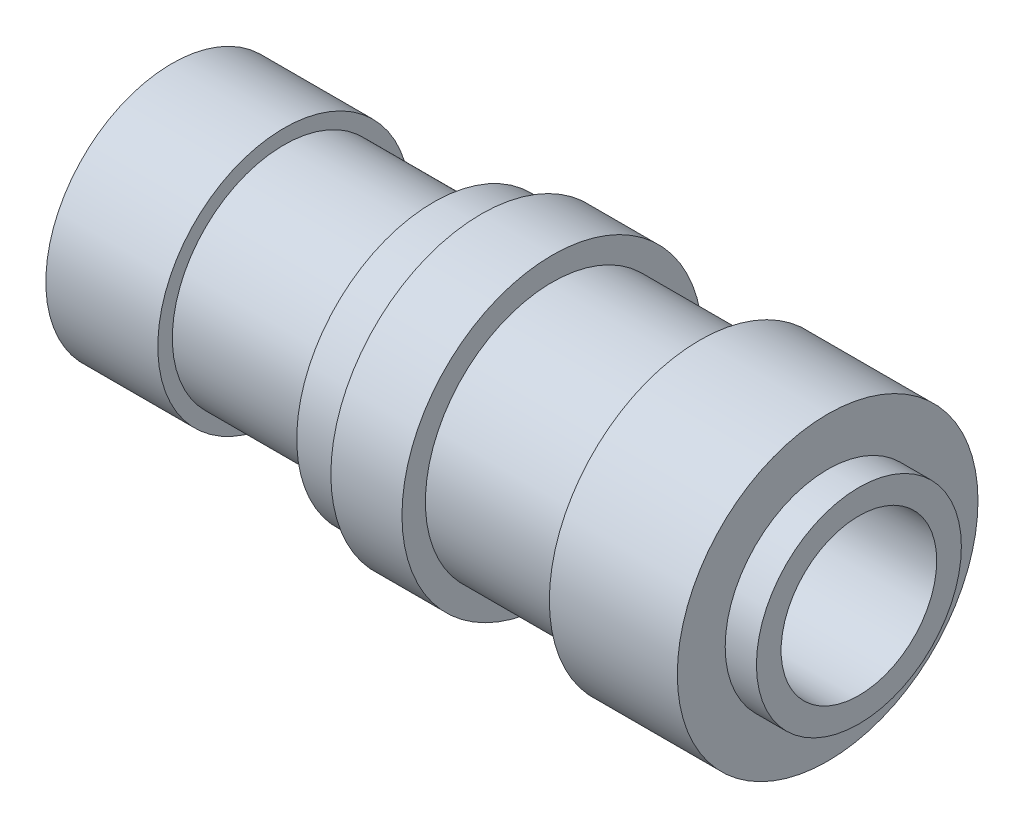
SolidWorks part; units mm, degrees
ref_plane "Front Plane" through (0, 0, 0) normal (0, 0, 1) x (1, 0, 0)
ref_plane "Top Plane" through (0, 0, 0) normal (0, 1, 0) x (1, 0, 0)
ref_plane "Right Plane" through (0, 0, 0) normal (1, 0, 0) x (0, 0, -1)
sketch "Sketch2" plane through (0, 0, 0) normal (0, 1, 0) x (1, 0, 0)
  line L0 (-5.8313, 11.938) -> (4.7671, 11.938)
  line L1 (4.7671, 11.938) -> (4.7671, 10.5639)
  line L2 (4.7671, 10.5639) -> (18.9277, 10.5639)
  line L3 (18.9277, 10.5639) -> (18.9277, 12.9487)
  line L4 (18.9277, 12.9487) -> (23.4413, 12.9487)
  line L5 (23.4413, 12.9487) -> (23.4413, 14.231)
  line L6 (23.4413, 14.231) -> (30.1707, 14.231)
  line L7 (30.1707, 14.231) -> (30.1707, 12.0134)
  line L8 (30.1707, 12.0134) -> (44.1219, 12.0134)
  line L9 (44.1219, 12.0134) -> (44.1219, 14.231)
  line L10 (44.1219, 14.231) -> (56.2352, 14.231)
  line L11 (56.2352, 14.231) -> (56.2352, 9.7)
  line L12 (56.2352, 9.7) -> (59.1927, 9.7)
  line L13 (59.1927, 9.7) -> (59.1927, 0)
  line L14 (59.1927, 0) -> (-5.8313, 0)
  line L15 (-5.8313, 0) -> (-5.8313, 11.938)
  dimension "D1" = 11.938
  dimension "D2" = 65.024
revolve "Revolve1" add sketch "Sketch2" angle 360 about L14
sketch "Sketch3" plane through (59.1927, 0, 0) normal (1, 0, 0) x (0, 0, -1)
  circle A0 centre (0, 0) radius 7.366
  dimension "D1" = 14.732
extrude "Cut-Extrude1" cut sketch "Sketch3" against normal through all both and the other way through all
